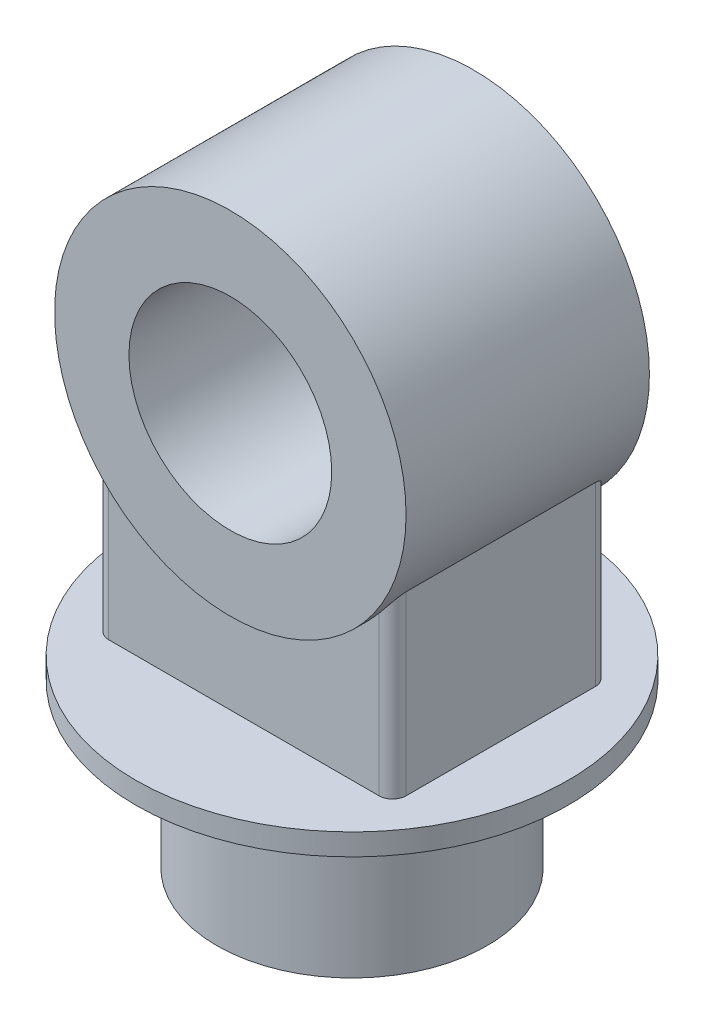
SolidWorks part; units mm, degrees
ref_plane "Front Plane" through (0, 0, 0) normal (0, 0, 1) x (1, 0, 0)
ref_plane "Top Plane" through (0, 0, 0) normal (0, 1, 0) x (1, 0, 0)
ref_plane "Right Plane" through (0, 0, 0) normal (1, 0, 0) x (0, 0, -1)
sketch "Sketch1" plane through (0, 0, 0) normal (0, 1, 0) x (1, 0, 0)
  circle A0 centre (0, 0) radius 100
  dimension "D1" = 200
extrude "Boss-Extrude1" add sketch "Sketch1" along normal blind 120
sketch "Sketch2" plane through (0, 120, 0) normal (0, 1, 0) x (1, 0, 0)
  circle A0 centre (0, 0) radius 160
  dimension "D1" = 320
extrude "Boss-Extrude2" add sketch "Sketch2" along normal blind 16
sketch "Sketch3" plane through (0, 0, 0) normal (0, 0, 1) x (1, 0, 0)
  line L0 (160, 136) -> (-160, 136) construction
  circle A0 centre (0, 336) radius 130
  circle A1 centre (0, 336) radius 75
  dimension "D1" = 260
  dimension "D2" = 150
  dimension "D3" = 200
extrude "Boss-Extrude4" add sketch "Sketch3" along normal mid plane 180 separate body
sketch "Sketch4" plane through (0, 136, 0) normal (0, 1, 0) x (1, 0, 0)
  line L1 (-110, 80) -> (110, 80)
  line L2 (-110, 80) -> (-110, -80)
  line L3 (-110, -80) -> (110, -80)
  line L4 (110, 80) -> (110, -80)
  line L5 (-110, 80) -> (110, -80) construction
  line L6 (-110, -80) -> (110, 80) construction
  point P0 (0, 0)
  dimension "D1" = 160
  dimension "D2" = 220
extrude "Boss-Extrude5" add sketch "Sketch4" along normal up to next
fillet "Fillet1" radius 10 4 edges at (-110, 201.359, -80) (110, 201.359, -80) (-110, 201.359, 80) (110, 201.359, 80)
